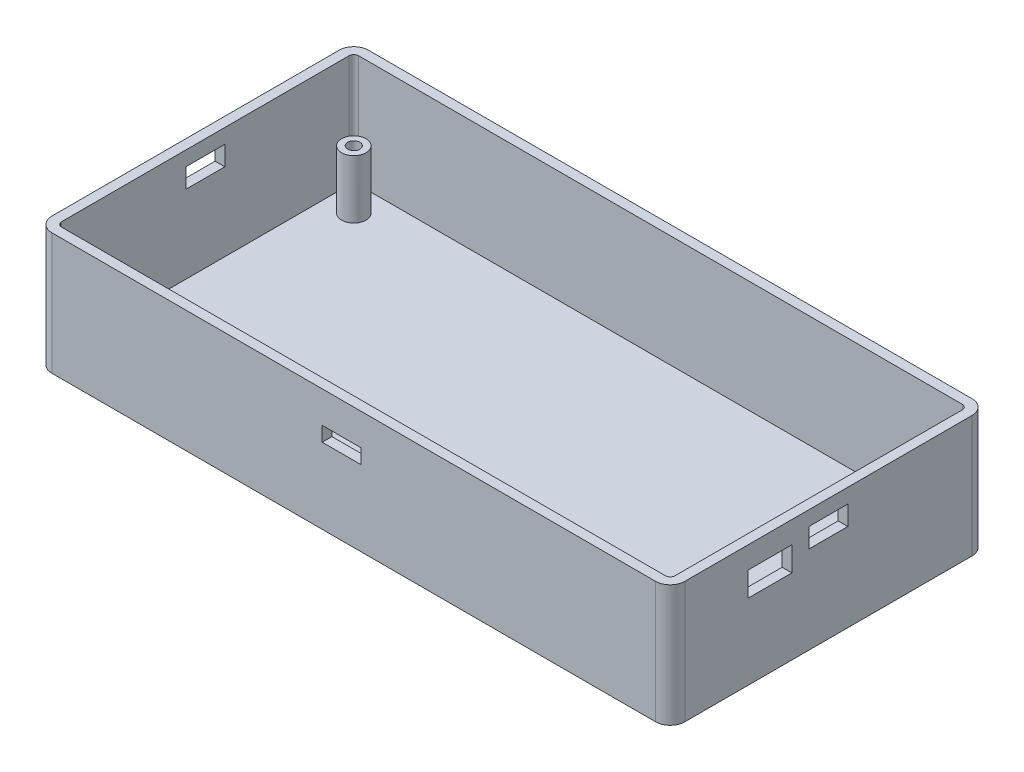
SolidWorks part; units mm, degrees
material "ABS"
ref_plane "Front Plane" through (0, 0, 0) normal (0, 0, 1) x (1, 0, 0)
ref_plane "Top Plane" through (0, 0, 0) normal (0, 1, 0) x (1, 0, 0)
ref_plane "Right Plane" through (0, 0, 0) normal (1, 0, 0) x (0, 0, -1)
sketch "Эскиз1" plane through (0, 0, 0) normal (0, 1, 0) x (1, 0, 0)
  line L1 (-65, -32.5) -> (65, -32.5)
  line L2 (-65, -32.5) -> (-65, 32.5)
  line L3 (-65, 32.5) -> (65, 32.5)
  line L4 (65, -32.5) -> (65, 32.5)
  line L5 (-65, -32.5) -> (65, 32.5) construction
  line L6 (-65, 32.5) -> (65, -32.5) construction
  point P0 (0, 0)
extrude "Бобышка-Вытянуть1" add sketch "Эскиз1" along normal blind 25
sketch "Эскиз2" plane through (0, 25, 0) normal (0, 1, 0) x (1, 0, 0)
  line L1 (-63, -30.5) -> (63, -30.5)
  line L2 (-63, -30.5) -> (-63, 30.5)
  line L3 (-63, 30.5) -> (63, 30.5)
  line L4 (63, -30.5) -> (63, 30.5)
  line L5 (-63, -30.5) -> (63, 30.5) construction
  line L6 (-63, 30.5) -> (63, -30.5) construction
  point P0 (0, 0)
extrude "Вырез-Вытянуть1" cut sketch "Эскиз2" against normal blind 23
sketch "Эскиз3" plane through (0, 2, 0) normal (0, 1, 0) x (1, 0, 0)
  line L0 (-63, 30.5) -> (-57.5, 30.5)
  line L1 (63, 30.5) -> (-63, 30.5) construction
  line L2 (-57.5, 30.5) -> (-57.5, 25)
  circle A0 centre (-57.5, 25) radius 2.5
extrude "Бобышка-Вытянуть2" add sketch "Эскиз3" along normal blind 12 contours A0
sketch "Эскиз5" plane through (65, 0, 0) normal (1, 0, 0) x (0, 0, -1)
  line L0 (0, 25) -> (0, 20)
  line L1 (-32.5, 25) -> (32.5, 25) construction
  line L3 (-4, 22) -> (4, 22)
  line L4 (-4, 22) -> (-4, 18)
  line L5 (-4, 18) -> (4, 18)
  line L6 (4, 22) -> (4, 18)
  line L7 (-4, 22) -> (4, 18) construction
  line L8 (-4, 18) -> (4, 22) construction
extrude "Вырез-Вытянуть3" cut sketch "Эскиз5" against normal blind 2
mirror "Зеркальное отражение5" about plane through (0, 0, 0) normal (1, 0, 0) of "Вырез-Вытянуть3"
sketch "Эскиз6" plane through (0, 0, 32.5) normal (0, 0, 1) x (1, 0, 0)
  line L0 (-65, 0) -> (-6.5, 0)
  line L1 (-65, 0) -> (65, 0) construction
  line L2 (-6.5, 0) -> (-6.5, 15.5)
  line L4 (-6.5, 15.5) -> (1.5, 15.5)
  line L5 (-6.5, 15.5) -> (-6.5, 18.5)
  line L6 (-6.5, 18.5) -> (1.5, 18.5)
  line L7 (1.5, 15.5) -> (1.5, 18.5)
extrude "Вырез-Вытянуть4" cut sketch "Эскиз6" against normal blind 2 contours L4 L7 L6 L5
sketch "Эскиз7" plane through (65, 0, 0) normal (1, 0, 0) x (0, 0, -1)
  line L0 (-32.5, 0) -> (-16.5, 0)
  line L1 (-32.5, 0) -> (32.5, 0) construction
  line L2 (-16.5, 0) -> (-16.5, 15.5)
  line L4 (-16.5, 15.5) -> (-7.5, 15.5)
  line L5 (-16.5, 15.5) -> (-16.5, 20.5)
  line L6 (-16.5, 20.5) -> (-7.5, 20.5)
  line L7 (-7.5, 15.5) -> (-7.5, 20.5)
extrude "Вырез-Вытянуть5" cut sketch "Эскиз7" against normal blind 2 contours L4 L7 L6 L5
sketch "Эскиз8" plane through (0, 14, 0) normal (0, 1, 0) x (1, 0, 0)
  circle A0 centre (-57.5, 25) radius 1.25
extrude "Вырез-Вытянуть6" cut sketch "Эскиз8" against normal blind 6
mirror "Зеркальное отражение6" about plane through (0, 0, 0) normal (1, 0, 0) of "Вырез-Вытянуть6", "Бобышка-Вытянуть2"
mirror "Зеркальное отражение7" about plane through (0, 0, 0) normal (0, 0, 1) of "Зеркальное отражение6", "Бобышка-Вытянуть2", "Вырез-Вытянуть6"
fillet "Скругление1" radius 1 4 edges at (63, 13.5, 30.5) (63, 13.5, -30.5) (-63, 13.5, -30.5) (-63, 13.5, 30.5)
fillet "Скругление2" radius 3 4 edges at (-65, 12.5, 32.5) (-65, 12.5, -32.5) (65, 12.5, -32.5) (65, 12.5, 32.5)
